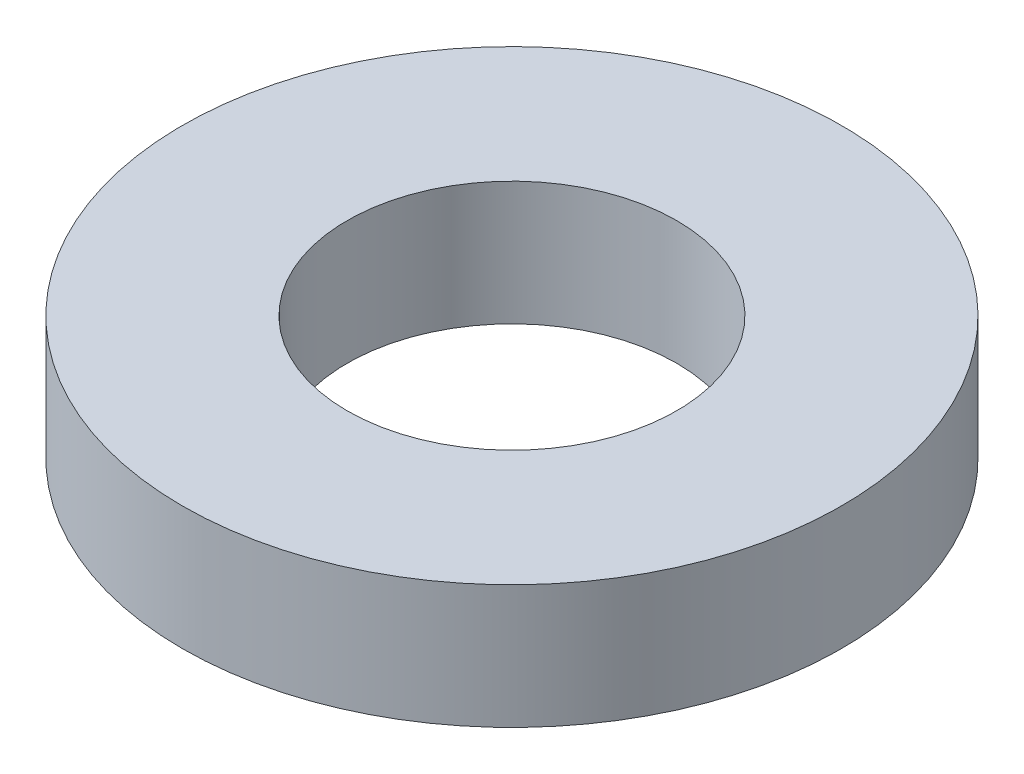
SolidWorks part; units mm, degrees
material "Delrin 2700 NC010, Low Viscosity Acetal Copolymer (SS)"
ref_plane "Front Plane" through (0, 0, 0) normal (0, 0, 1) x (1, 0, 0)
ref_plane "Top Plane" through (0, 0, 0) normal (0, 1, 0) x (1, 0, 0)
ref_plane "Right Plane" through (0, 0, 0) normal (1, 0, 0) x (0, 0, -1)
sketch "Sketch1" plane through (0, 0, 0) normal (0, 1, 0) x (1, 0, 0)
  circle A0 centre (0, 0) radius 1
  circle A1 centre (0, 0) radius 2
  dimension "D1" = 2
extrude "Boss-Extrude1" add sketch "Sketch1" along normal blind 0.75
